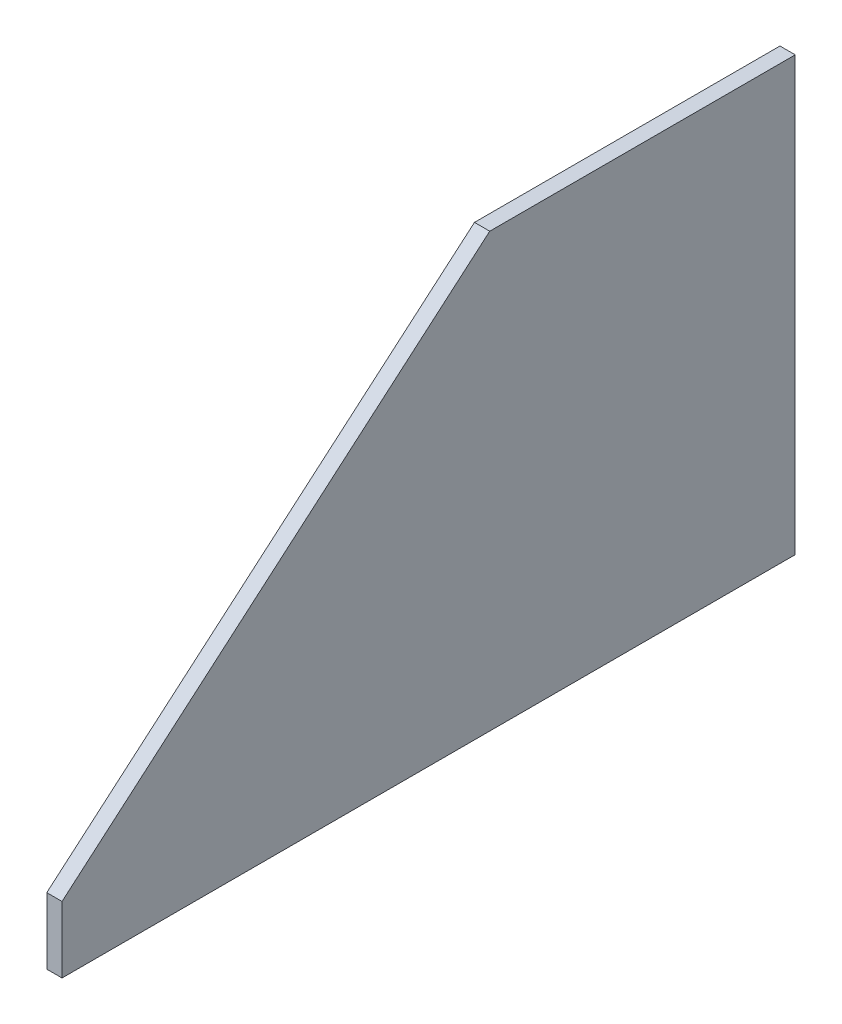
SolidWorks part; units mm, degrees
ref_plane "Plan de face" through (0, 0, 0) normal (0, 0, 1) x (1, 0, 0)
ref_plane "Plan de dessus" through (0, 0, 0) normal (0, 1, 0) x (1, 0, 0)
ref_plane "Plan de droite" through (0, 0, 0) normal (1, 0, 0) x (0, 0, -1)
sketch "Esquisse2" plane through (0, 0, 0) normal (1, 0, 0) x (0, 0, -1)
  line L0 (0, 0) -> (-304.8, 0)
  line L1 (-304.8, 0) -> (-127, 152.4)
  line L2 (-127, 152.4) -> (0, 152.4)
  line L3 (0, 152.4) -> (0, 0)
  line L4 (0, -27.559) -> (-304.8, -27.559)
  line L5 (-304.8, -27.559) -> (-304.8, 0)
  line L6 (0, -27.559) -> (0, 0)
  dimension "D1" = 27.559
  dimension "D2" = 152.4
  dimension "D3" = 127
  dimension "D4" = 304.8
extrude "Boss.-Extru.1" add sketch "Esquisse2" along normal blind 6.35 contours L3 L2 L1 L0 | L4 L6 L0 L5
